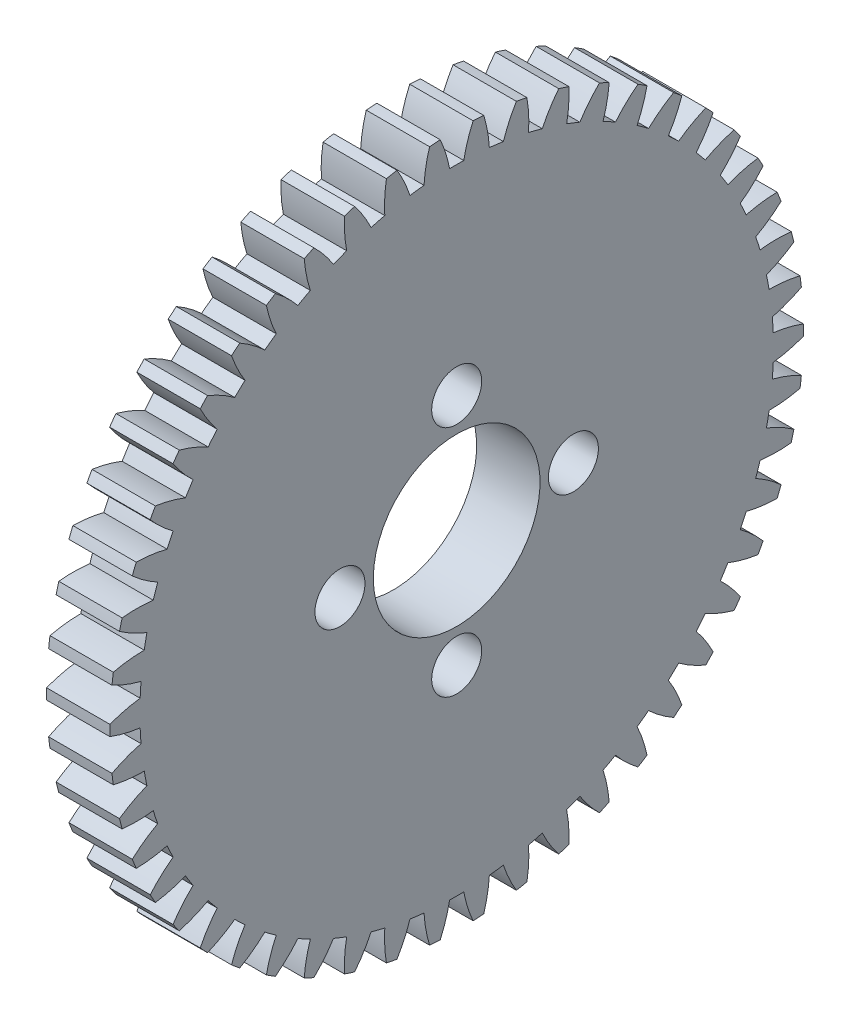
SolidWorks part; units mm, degrees
ref_plane "Plane1" through (0, 0, 0) normal (0, 0, 1) x (1, 0, 0)
ref_plane "Plane2" through (0, 0, 0) normal (0, 1, 0) x (1, 0, 0)
ref_plane "Plane3" through (0, 0, 0) normal (1, 0, 0) x (0, 0, -1)
other "Configuration Table"
sketch "HoldingSke" plane through (0, 0, 0) normal (0, 1, 0) x (1, 0, 0)
  line L0 (0, 0) -> (0.8035, -0.9576)
  line L1 (-15, 0) -> (100, 0) construction
  line L2 (0, 0) -> (-2.1039, 2.3779)
  line L3 (0, 0) -> (-11.863, 4.5341)
  line L4 (0, 0) -> (5.5511, 6.6156)
  line L5 (0, 0) -> (-46.8476, -17.4728)
  line L6 (0, 0) -> (-3.1501, -2.1254)
  line L7 (-2.1039, 2.3779) -> (8.6586, 51.2059)
  line L8 (-76.2, 54.61) -> (-76.1, 54.61)
  line L9 (-67.7845, 28.3722) -> (-49.3413, 33.142)
  line L10 (-76.2, 71.12) -> (104.1128, 71.12)
  line L11 (0, 0) -> (-3.8, 0)
  line L12 (-76.2, 101.6) -> (-76.17, 101.6)
  line L13 (24.9733, 27.94) -> (52.9518, 28.4284)
  line L14 (24.9733, 27.94) -> (24.9743, 27.94)
  line L15 (24.9733, 27.94) -> (100.4006, 29.5858)
  line L16 (-63.627, -0.8) -> (-12.827, -0.8)
  circle A0 centre (0, 0) radius 0.4
  circle A1 centre (0, 0) radius 18.999
  circle A2 centre (0, 0) radius 37.5
  circle A3 centre (0, 0) radius 0.4
  dimension "MHD" = 37.998
  dimension "Hub_dia" = 75
  dimension "Bore" = 0.8
  dimension "MBD" = 0.8
  dimension "Num_teeth" = 50
  dimension "Pitch" = 1.25
  dimension "Overall_len" = 50
  dimension "Show_teeth" = 50
  dimension "Thickness" = 3.8
  dimension "OAL" = 50.0001
  dimension "T_dim" = 0.1
  dimension "Ap" = 14.5
  dimension "H" = 19.05
  dimension "Pitch_radius" = 180.3128
  dimension "Width" = 3.8
  dimension "Backlash" = 0.03
  dimension "Addendum_fac" = 1
  dimension "Dedendum_fac" = 1.25
  dimension "Clearance_fac" = 0.25
  dimension "Dedendum_add" = 0.001
  dimension "Module" = 0.8
sketch "BasProSke" plane through (0, 0, 0) normal (0, 1, 0) x (1, 0, 0)
  line L0 (-10, 0) -> (60, 0) construction
  line L1 (0, 0) -> (0, 20.8)
  line L2 (0, 0) -> (3.8, 0)
  line L3 (3.8, 0) -> (3.8, 20.8)
  line L4 (3.8, 20.8) -> (0, 20.8)
  dimension "Thickness" = 3.8
  dimension "Diameter" = 41.6
revolve "Base-Revolve" add sketch "BasProSke" angle 360 about L0
sketch "TooCutSke" plane through (0, 0, 0) normal (1, 0, 0) x (0, 0, -1)
  line L1 (0, 0) -> (0, 107) construction
  line L2 (0, 0) -> (-0.6807, 19.9884) construction
  line L3 (0, 0) -> (-2.5106, 39.9045) construction
  line L4 (-0.6807, 19.9884) -> (-1.2553, 19.9523) construction
  arc A0 (0.4248, 18.9942) -> (-0.4248, 18.9942) centre (0, 0) ccw
  arc A1 (0.9967, 20.8015) -> (-0.9967, 20.8015) centre (0, 0) ccw
  circle A2 centre (0, 0) radius 20 construction
  circle A3 centre (0, 0) radius 19.363 construction
  arc A4 (-0.4248, 18.9942) -> (-0.9967, 20.8015) centre (-8.2843, 17.5013) ccw
  arc A5 (0.9967, 20.8015) -> (0.4248, 18.9942) centre (8.2843, 17.5013) ccw
  dimension "Root_dia" = 37.998
  dimension "Overcut_dia" = 41.6508
  dimension "Pitch_dia" = 40
  dimension "Base_dia" = 38.7259
  dimension "Flank_rad" = 8
  dimension "Half_ang" = 3.6
  dimension "Half_CT" = 0.5757
extrude "ToothCut" cut sketch "TooCutSke" along normal through all
fillet "Breaks" [suppressed] radius 0.016
fillet "RootFillets" [suppressed] radius 0.201
pattern_circular "TeethCuts" count 50 every 7.2 about axis through (-10, 0, 0) along (1, 0, 0) of "ToothCut", "RootFillets", "Breaks"
sketch "HubNeaOneSke" plane through (0, 0, 0) normal (-1, 0, 0) x (0, 0, 1)
  circle A0 centre (0, 0) radius 18.999
  dimension "Diameter" = 37.998
extrude "HubNearOne" [suppressed] add sketch "HubNeaOneSke" along normal blind 46.2001
sketch "HubNeaBotSke" plane through (0, 0, 0) normal (-1, 0, 0) x (0, 0, 1)
  circle A0 centre (0, 0) radius 18.999
  dimension "Diameter" = 37.998
extrude "HubNearBoth" [suppressed] add sketch "HubNeaBotSke" along normal blind 23.1
ref_plane "FarPln" through (3.8, 0, 0) normal (1, 0, 0) x (0, 0, -1)
sketch "HubFarSke" plane through (3.8, 0, 0) normal (1, 0, 0) x (0, 0, -1)
  circle A0 centre (0, 0) radius 18.999
  dimension "Diameter" = 37.998
extrude "HubFar" [suppressed] add sketch "HubFarSke" along normal blind 23.1
sketch "BorSke" plane through (0, 0, 0) normal (1, 0, 0) x (0, 0, -1)
  circle A0 centre (0, 0) radius 0.4
  dimension "Diameter" = 0.8
extrude "Bore" cut sketch "BorSke" along normal mid plane 100.0001
sketch "KeySke" plane through (0, 0, 0) normal (1, 0, 0) x (0, 0, -1)
  line L0 (-0.05, 0) -> (-0.05, 0.5)
  line L1 (-0.05, 0.5) -> (0.05, 0.5)
  line L2 (0.05, 0.5) -> (0.05, 0)
  line L3 (0, 0) -> (0, 34) construction
  line L4 (-0.05, 0) -> (0.05, 0)
  dimension "Offset" = 0.5
  dimension "Width" = 0.1
extrude "Keyway" [suppressed] cut sketch "KeySke" along normal mid plane 100.0001
pattern_circular "Keyway2" [suppressed] count 2 every 90 about axis through (-10, 0, 0) along (1, 0, 0)
sketch "草图1" plane through (0, 0, 0) normal (-1, 0, 0) x (0, 0, 1)
  line L0 (0, 0) -> (0, 14.2002) construction
  line L1 (0, 0) -> (0, -9.2943) construction
  line L2 (0, 0) -> (-16.0976, 0) construction
  line L3 (0, 0) -> (18.1566, 0) construction
  circle A1 centre (0, 0) radius 5
  circle A2 centre (0, 7) radius 1.5
  circle A4 centre (-7, 0) radius 1.5
  circle A5 centre (0, -7) radius 1.5
  circle A6 centre (7, 0) radius 1.5
  dimension "D1" = 10
  dimension "D2" = 3
  dimension "D3" = 7
  dimension "D4" = 7
  dimension "D5" = 0
  dimension "D6" = 0
extrude "切除-拉伸1" cut sketch "草图1" against normal blind 3.8
equation "' \"Module@HoldingSke\" = 6.35"
equation "' \"Num_teeth@HoldingSke\" = 12"
equation "' \"Ap@HoldingSke\" =  20"
equation "' \"Ap@HoldingSke\" = 20"
equation "' \"Width@HoldingSke\" = 0.5 * 25.4"
equation "' \"Hub_dia@HoldingSke\"= 1 * 25.4"
equation "' \"Hub_dia@HoldingSke\" = 1 * 25.4"
equation "' \"Overall_len@HoldingSke\" = 1.0 * 25.4"
equation "' \"Bore@HoldingSke\" = 0.75 * 25.4"
equation "' \"T_dim@HoldingSke\" = 0.1 * 25.4"
equation "' \"Width@KeySke\" = 0.25 * 25.4"
equation "' \"Show_teeth@HoldingSke\" = 13"
equation "' \"Backlash@HoldingSke\" = 0.009 * 25.4"
equation "' \"Addendum_fac@HoldingSke\" = 1.0"
equation "' \"Dedendum_fac@HoldingSke\" = 1.25"
equation "' \"Dedendum_add@HoldingSke\" = 0.00005 * 25.4"
equation "' \"Clearance_fac@HoldingSke\" = 0.25"
equation "\"Pitch@HoldingSke\" = 1 / \"Module@HoldingSke\""
equation "\"Overcut_dia@TooCutSke\" = (\"Num_teeth@HoldingSke\" + 2 * \"Addendum_fac@HoldingSke\") / \"Pitch@HoldingSke\" + 0.002 * 25.4"
equation "\"Pitch_dia@TooCutSke\" = \"Num_teeth@HoldingSke\" / \"Pitch@HoldingSke\""
equation "\"Base_dia@TooCutSke\" = \"Num_teeth@HoldingSke\" / \"Pitch@HoldingSke\" * cos((\"Ap@HoldingSke\"  * 3.14159265 / 180))"
equation "\"Root_dia@TooCutSke\" = (\"Num_teeth@HoldingSke\" + 2) / \"Pitch@HoldingSke\" - 2 * (\"Addendum_fac@HoldingSke\" + \"Dedendum_fac@HoldingSke\") / \"Pitch@HoldingSke\" - \"Dedendum_add@HoldingSke\" * 2"
equation "\"Half_ang@TooCutSke\" = 180 / \"Num_teeth@HoldingSke\""
equation "\"Half_CT@TooCutSke\" = \"Num_teeth@HoldingSke\" / \"Pitch@HoldingSke\" * sin((3.14159265 / 2 / \"Num_teeth@HoldingSke\")) / 2 - 7 * \"Backlash@HoldingSke\" / 4"
equation "\"Flank_rad@TooCutSke\" = \"Num_teeth@HoldingSke\" / \"Pitch@HoldingSke\" / 5"
equation "\"Radius@RootFillets\" = \"Clearance_fac@HoldingSke\" / \"Pitch@HoldingSke\" + \"Dedendum_add@HoldingSke\""
equation "\"Break_rad@Breaks\" = 0.02 / \"Pitch@HoldingSke\""
equation "\"Thickness@HoldingSke\" = \"Width@HoldingSke\""
equation "\"OAL@HoldingSke\" = \"Thickness@HoldingSke\""
equation "\"MHD@HoldingSke\" = (\"Num_teeth@HoldingSke\" + 2) / \"Pitch@HoldingSke\" - 2 * (\"Addendum_fac@HoldingSke\" + \"Dedendum_fac@HoldingSke\")  / \"Pitch@HoldingSke\" - \"Dedendum_add@HoldingSke\" * 2"
equation "\"MBD@HoldingSke\" = (\"Num_teeth@HoldingSke\" + 2) / \"Pitch@HoldingSke\" - 2 * (\"Addendum_fac@HoldingSke\" + \"Dedendum_fac@HoldingSke\")  / \"Pitch@HoldingSke\" - \"Dedendum_add@HoldingSke\" * 2 - 0.002 * 25.4"
equation "\"MHD@HoldingSke\" = ((sgn( \"MHD@HoldingSke\" - \"Hub_dia@HoldingSke\" )-1)*( \"MHD@HoldingSke\" - \"Hub_dia@HoldingSke\" ))/-2+ \"Hub_dia@HoldingSke\""
equation "\"MBD@HoldingSke\" = ((sgn( \"MBD@HoldingSke\" - \"Bore@HoldingSke\" )-1)*( \"MBD@HoldingSke\" - \"Bore@HoldingSke\" ))/-2+ \"Bore@HoldingSke\""
equation "\"OAL@HoldingSke\" = ((sgn( \"OAL@HoldingSke\" - \"Overall_len@HoldingSke\" )+1)*( \"OAL@HoldingSke\" - \"Overall_len@HoldingSke\" ))/2 + \"Overall_len@HoldingSke\" + 0.000002 * 25.4"
equation "\"Num_teeth@TeethCuts\" = int( \"Show_teeth@HoldingSke\" ) + 1"
equation "\"Num_teeth@TeethCuts\" = ((sgn( \"Num_teeth@TeethCuts\" - \"Num_teeth@HoldingSke\" )-1)*( \"Num_teeth@TeethCuts\" - \"Num_teeth@HoldingSke\" ))/-2+ \"Num_teeth@HoldingSke\""
equation "\"Num_teeth@TeethCuts\" = ((sgn( \"Num_teeth@TeethCuts\" - 2.0)+1)*( \"Num_teeth@TeethCuts\" - 2.0))/2 +2.0"
equation "\"Angle@TeethCuts\" = 360.0 / \"Num_teeth@HoldingSke\""
equation "\"Diameter@BasProSke\" = (\"Num_teeth@HoldingSke\" + 2 * \"Addendum_fac@HoldingSke\") / \"Pitch@HoldingSke\""
equation "\"Thickness@BasProSke\"  = \"Thickness@HoldingSke\""
equation "' \"Fillet_rad@BasProSke\" =  \"Thickness@HoldingSke\" * 0.05"
equation "' \"Fillet_rad@BasProSke\" = \"Thickness@HoldingSke\" * 0.05"
equation "\"MHD@HoldingSke\" = ((sgn( \"MHD@HoldingSke\" - \"Root_dia@TooCutSke\" )-1)*( \"MHD@HoldingSke\" - \"Root_dia@TooCutSke\" ))/-2+ \"Root_dia@TooCutSke\""
equation "\"Diameter@HubNeaOneSke\" = \"MHD@HoldingSke\""
equation "\"Length@HubNearOne\" = \"OAL@HoldingSke\" - \"Thickness@BasProSke\""
equation "\"Diameter@HubNeaBotSke\" = \"MHD@HoldingSke\""
equation "\"Length@HubNearBoth\" = ( \"OAL@HoldingSke\" - \"Thickness@BasProSke\" ) / 2.0"
equation "\"Thickness@FarPln\" = \"Thickness@BasProSke\""
equation "\"Diameter@HubFarSke\" = \"MHD@HoldingSke\""
equation "\"Length@HubFar\" = ( \"OAL@HoldingSke\" - \"Thickness@BasProSke\" ) / 2.0"
equation "\"Diameter@BorSke\" = \"MBD@HoldingSke\""
equation "\"D1@Bore\" = \"OAL@HoldingSke\" * 2.0"
equation "\"D1@Keyway\" = \"OAL@HoldingSke\" * 2.0"
equation "\"Offset@KeySke\" = \"T_dim@HoldingSke\" + \"MBD@HoldingSke\" / 2.0"
